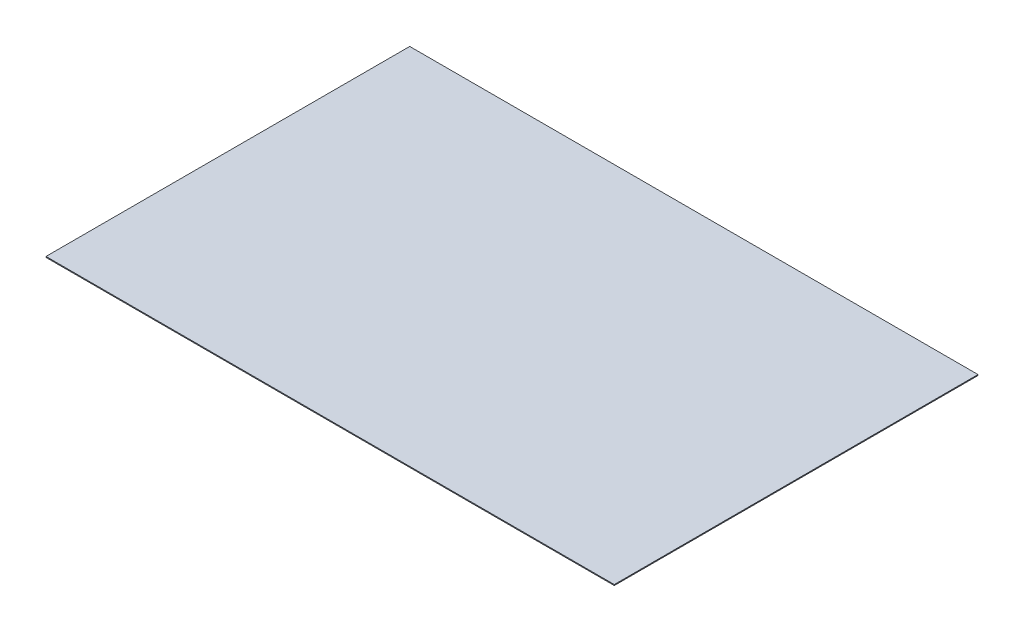
SolidWorks part; units mm, degrees
ref_plane "Спереди" through (0, 0, 0) normal (0, 0, 1) x (1, 0, 0)
ref_plane "Сверху" through (0, 0, 0) normal (0, 1, 0) x (1, 0, 0)
ref_plane "Справа" through (0, 0, 0) normal (1, 0, 0) x (0, 0, -1)
sketch "MASTER_FOOTPRINT" plane through (0, 0, 0) normal (0, 1, 0) x (1, 0, 0)
  line L1 (0, 0) -> (1250, 0)
  line L2 (0, 0) -> (0, 800)
  line L3 (0, 800) -> (1250, 800)
  line L4 (1250, 0) -> (1250, 800)
  dimension "D1" = 1250
  dimension "D2" = 800
extrude "BATH_BASE_PLATE" add sketch "MASTER_FOOTPRINT" along normal blind 2
equation "\"AI_Q_Peak\"= 0.006"
equation "\"AI_B_Bath\" = 800"
equation "\"AI_L_Settle\" = 800"
equation "\"AI_L_Inlet\"= 250"
equation "\"AI_L_Outlet\"= 200"
equation "\"AI_L_Bath\" = 1250"
equation "\"AI_H_Water\"= 550"
equation "\"AI_H_Freeboard\"= 200"
equation "\"AI_H_Bath\"= 750"
equation "\"AI_Shell_Thickness\"= 2"
equation "\"AI_Inlet_DN\"= 100"
equation "\"AI_Weir_Width\"= 600"
equation "\"AI_Inlet_Baffle_Offset\"= 125"
equation "\"AI_Distributor_Open_Area\"= 0.28"
equation "\"AI_Distributor_Hole_Dia\"= 22"
equation "\"AI_Distributor_Blind_Zone\"= 110"
equation "\"AI_Outlet_Baffle_Depth\"= 250"
equation "\"AI_Screw_Diameter\"= 100"
equation "\"AI_Screw_Pitch\"= 100"
equation "\"AI_Screw_Angle\"= 30"
equation "\"AI_Screw_Rpm\"= 15"
equation "\"AI_Screw_Clearance\"= 5"
equation "\"AI_Liner_Thickness\"= 5"
equation "\"AI_Discharge_Height\"= 650"
equation "\"AI_Frame_Height\"= 500"
equation "\"D1@MASTER_FOOTPRINT\" = \"AI_L_Bath\""
equation "\"D2@MASTER_FOOTPRINT\" = \"AI_B_Bath\""
